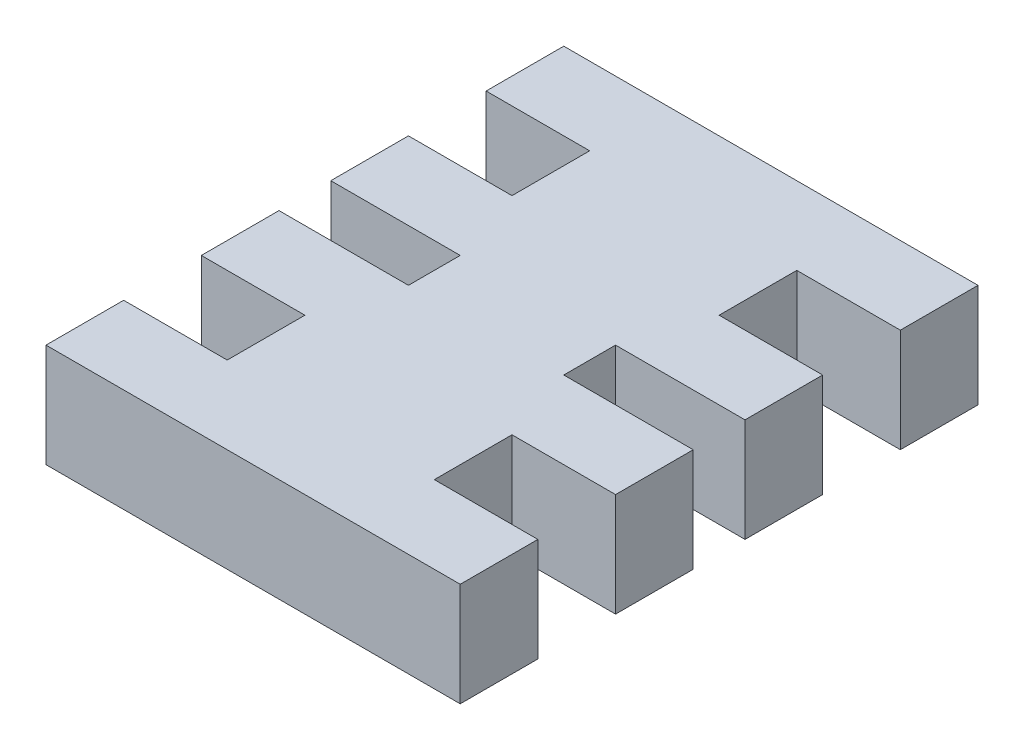
SolidWorks part; units mm, degrees
ref_plane "Front Plane" through (0, 0, 0) normal (0, 0, 1) x (1, 0, 0)
ref_plane "Top Plane" through (0, 0, 0) normal (0, 1, 0) x (1, 0, 0)
ref_plane "Right Plane" through (0, 0, 0) normal (1, 0, 0) x (0, 0, -1)
sketch "Sketch1" plane through (0, 0, 0) normal (0, 1, 0) x (1, 0, 0)
  line L0 (0, 50) -> (0, -50) construction
  line L1 (-40, 50) -> (40, 50)
  line L2 (-40, 50) -> (-40, 35)
  line L3 (-40, -50) -> (40, -50)
  line L4 (40, 50) -> (40, 35)
  line L5 (-40, 50) -> (40, -50) construction
  line L6 (-40, -50) -> (40, 50) construction
  line L7 (-40, 35) -> (-20, 35)
  line L9 (-40, 20) -> (-20, 20)
  line L10 (-20, 35) -> (-20, 20)
  line L11 (-40, 0) -> (40, 0) construction
  line L12 (40, 20) -> (20, 20)
  line L13 (20, 35) -> (20, 20)
  line L14 (40, 35) -> (20, 35)
  line L15 (40, -35) -> (20, -35)
  line L16 (20, -35) -> (20, -20)
  line L17 (40, -20) -> (20, -20)
  line L18 (-40, -20) -> (-20, -20)
  line L19 (-40, -35) -> (-20, -35)
  line L20 (-20, -35) -> (-20, -20)
  line L21 (40, -5) -> (15, -5)
  line L22 (-40, 5) -> (-15, 5)
  line L24 (-40, -5) -> (-15, -5)
  line L25 (-15, 5) -> (-15, -5)
  line L26 (15, 5) -> (15, -5)
  line L27 (40, 5) -> (15, 5)
  line L28 (-40, 20) -> (-40, 5)
  line L29 (-40, -5) -> (-40, -20)
  line L30 (-40, -35) -> (-40, -50)
  line L31 (40, -35) -> (40, -50)
  line L32 (40, -5) -> (40, -20)
  line L33 (40, 20) -> (40, 5)
  point P0 (0, 0)
  dimension "D1" = 80
  dimension "D2" = 100
  dimension "D3" = 20
  dimension "D4" = 15
  dimension "D5" = 15
  dimension "D6" = 25
  dimension "D7" = 10
  dimension "D8" = 45
  dimension "D9" = 15
extrude "Boss-Extrude1" add sketch "Sketch1" along normal blind 20
